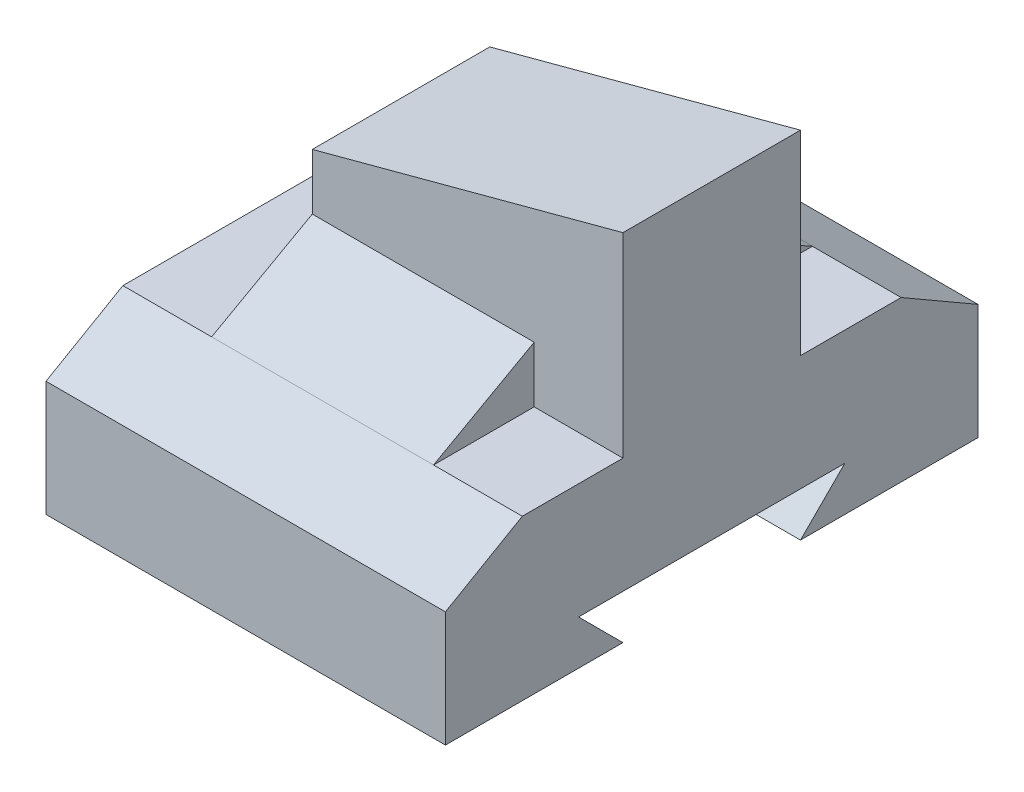
SolidWorks part; units mm, degrees
ref_plane "Plano frontal" through (0, 0, 0) normal (0, 0, 1) x (1, 0, 0)
ref_plane "Plano superior" through (0, 0, 0) normal (0, 1, 0) x (1, 0, 0)
ref_plane "Plano direito" through (0, 0, 0) normal (1, 0, 0) x (0, 0, -1)
sketch "Esboço1" plane through (0, 0, 0) normal (1, 0, 0) x (0, 0, -1)
  line L0 (-40, 0) -> (-45, 5)
  line L1 (-45, 5) -> (-15, 5)
  line L2 (-15, 5) -> (-20, 0)
  line L3 (-20, 0) -> (0, 0)
  line L4 (0, 0) -> (0, 13)
  line L5 (0, 13) -> (-8.6603, 18)
  line L6 (-8.6603, 18) -> (-51.3397, 18)
  line L7 (-51.3397, 18) -> (-60, 13)
  line L8 (-60, 13) -> (-60, 0)
  line L9 (-60, 0) -> (-40, 0)
  point P8 (-38.0195, 35.8959)
  point P11 (0, 0)
  dimension "D1" = 20
  dimension "D2" = 20
  dimension "D3" = 60
  dimension "D4" = 13
  dimension "D5" = 60
  dimension "D6" = 5
  dimension "D7" = 45
  dimension "D8" = 18
  dimension "D9" = 60
extrude "Ressalto-extrusão1" add sketch "Esboço1" against normal blind 45
sketch "Esboço2" plane through (0, 0, 0) normal (1, 0, 0) x (0, 0, -1)
  line L0 (-40, 18) -> (-40, 40)
  line L1 (-8.6603, 18) -> (-51.3397, 18) construction
  line L2 (-40, 40) -> (-20, 40)
  line L3 (-20, 40) -> (-20, 18)
  line L4 (-40, 18) -> (-20, 18)
  line L5 (-60, 13) -> (-60, 0) construction
  dimension "D1" = 20
  dimension "D2" = 20
  dimension "D3" = 22
extrude "Ressalto-extrusão2" add sketch "Esboço2" against normal blind 35
sketch "Esboço3" plane through (0, 0, 40) normal (0, 0, 1) x (1, 0, 0)
  line L0 (0, 40) -> (-35, 30.6218)
  line L1 (-35, 40) -> (0, 40) construction
  line L2 (-35, 40) -> (-35, 18) construction
  line L3 (-35, 30.6218) -> (-35, 40)
  line L4 (-35, 40) -> (0, 40)
  dimension "D1" = 105
extrude "Corte-extrusão1" cut sketch "Esboço3" against normal up to next
sketch3d "3DSketch1" plane through (0, 0, 0) normal (0, 0, 1) x (1, 0, 0)
  dimension "D1" = 10
sketch "Esboço4" plane through (-35, 0, 0) normal (-1, 0, 0) x (0, 0, 1)
  line L0 (8.6603, 18) -> (20, 24.3109)
  line L1 (20, 18) -> (20, 30.6218) construction
  line L2 (20, 24.3109) -> (20, 18)
  line L3 (20, 18) -> (8.6603, 18)
  line L4 (51.3397, 18) -> (40, 24.3109)
  line L5 (40, 30.6218) -> (40, 18) construction
  line L6 (40, 24.3109) -> (40, 18)
  line L7 (40, 18) -> (51.3397, 18)
extrude "Ressalto-extrusão3" add sketch "Esboço4" against normal blind 25 separate body
